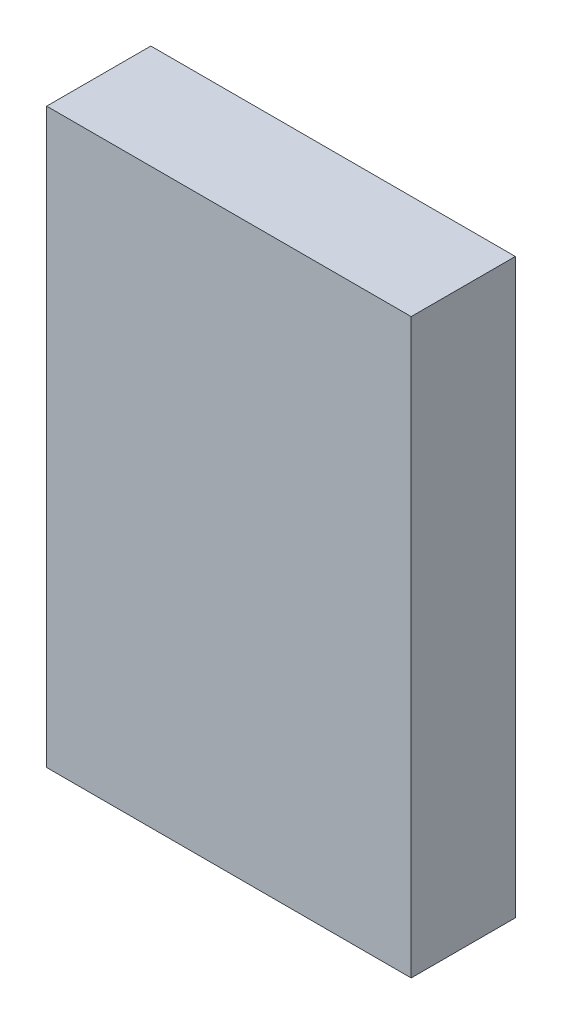
SolidWorks part; units mm, degrees
ref_plane "Front Plane" through (0, 0, 0) normal (0, 0, 1) x (1, 0, 0)
ref_plane "Top Plane" through (0, 0, 0) normal (0, 1, 0) x (1, 0, 0)
ref_plane "Right Plane" through (0, 0, 0) normal (1, 0, 0) x (0, 0, -1)
sketch "Sketch1" plane through (0, 0, 0) normal (0, 0, 1) x (1, 0, 0)
  line L1 (-7, -11) -> (7, -11)
  line L2 (-7, -11) -> (-7, 11)
  line L3 (-7, 11) -> (7, 11)
  line L4 (7, -11) -> (7, 11)
  line L5 (-7, -11) -> (7, 11) construction
  line L6 (-7, 11) -> (7, -11) construction
  point P0 (0, 0)
  dimension "D1" = 14
  dimension "D2" = 22
extrude "Boss-Extrude1" add sketch "Sketch1" along normal mid plane 4
